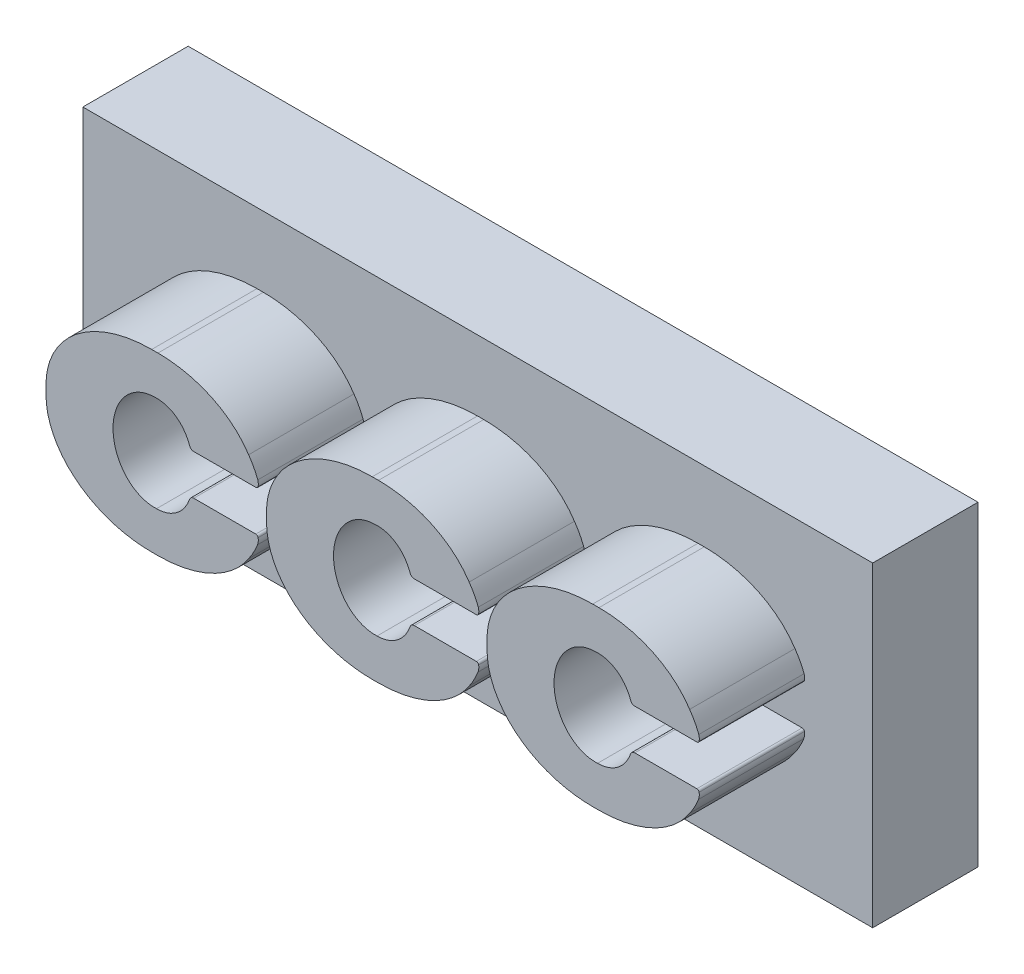
SolidWorks part; units mm, degrees
ref_plane "Front Plane" through (0, 0, 0) normal (0, 0, 1) x (1, 0, 0)
ref_plane "Top Plane" through (0, 0, 0) normal (0, 1, 0) x (1, 0, 0)
ref_plane "Right Plane" through (0, 0, 0) normal (1, 0, 0) x (0, 0, -1)
sketch "Sketch2" plane through (0, 0, 0) normal (0, 0, 1) x (1, 0, 0)
  line L0 (11.9717, 19.7341) -> (13.1563, 19.7341)
  line L1 (11.2915, 21.0135) -> (11.173, 21.0135)
  line L2 (9.1659, 19.4298) -> (9.1659, 19.265)
  line L3 (11.173, 17.6813) -> (11.2915, 17.6813)
  line L4 (13.1506, 18.9656) -> (11.9717, 18.9656)
  line L5 (7.784, 19.7341) -> (8.9686, 19.7341)
  line L6 (7.1038, 21.0135) -> (6.9853, 21.0135)
  line L7 (4.9781, 19.4298) -> (4.9781, 19.265)
  line L8 (6.9853, 17.6813) -> (7.1038, 17.6813)
  line L9 (8.9629, 18.9656) -> (7.784, 18.9656)
  line L10 (16.1595, 19.7341) -> (17.3441, 19.7341)
  line L11 (15.4793, 21.0135) -> (15.3608, 21.0135)
  line L12 (13.3536, 19.4298) -> (13.3536, 19.265)
  line L13 (15.3608, 17.6813) -> (15.4793, 17.6813)
  line L14 (17.3383, 18.9656) -> (16.1595, 18.9656)
  arc A0 (11.8937, 19.7892) -> (11.9717, 19.7341) centre (11.9717, 19.8169) ccw
  arc A1 (13.1563, 19.7341) -> (13.1934, 19.7655) centre (13.1507, 19.7782) ccw
  arc A2 (13.1934, 19.7655) -> (13.1881, 19.8762) centre (12.9648, 19.8101) ccw
  arc A3 (13.1881, 19.8762) -> (13.0144, 20.2019) centre (11.8185, 19.3553) ccw
  arc A4 (13.0144, 18.4929) -> (13.1821, 18.8047) centre (11.8303, 19.3304) ccw
  arc A5 (13.1821, 18.8047) -> (13.1945, 18.9287) centre (12.965, 18.8891) ccw
  arc A6 (13.1945, 18.9287) -> (13.1506, 18.9656) centre (13.1506, 18.9211) ccw
  arc A7 (11.9717, 18.9656) -> (11.8937, 18.9105) centre (11.9717, 18.8828) ccw
  arc A8 (7.7059, 19.7892) -> (7.784, 19.7341) centre (7.784, 19.8169) ccw
  arc A9 (8.9686, 19.7341) -> (9.0056, 19.7655) centre (8.963, 19.7782) ccw
  arc A10 (9.0056, 19.7655) -> (9.0003, 19.8762) centre (8.777, 19.8101) ccw
  arc A11 (9.0003, 19.8762) -> (8.8267, 20.2019) centre (7.6307, 19.3553) ccw
  arc A12 (8.8267, 18.4929) -> (8.9943, 18.8047) centre (7.6426, 19.3304) ccw
  arc A13 (8.9943, 18.8047) -> (9.0068, 18.9287) centre (8.7773, 18.8891) ccw
  arc A14 (9.0068, 18.9287) -> (8.9629, 18.9656) centre (8.9629, 18.9211) ccw
  arc A15 (7.784, 18.9656) -> (7.7059, 18.9105) centre (7.784, 18.8828) ccw
  arc A16 (16.0814, 19.7892) -> (16.1595, 19.7341) centre (16.1595, 19.8169) ccw
  arc A17 (17.3441, 19.7341) -> (17.3811, 19.7655) centre (17.3384, 19.7782) ccw
  arc A18 (17.3811, 19.7655) -> (17.3758, 19.8762) centre (17.1525, 19.8101) ccw
  arc A19 (17.3758, 19.8762) -> (17.2022, 20.2019) centre (16.0062, 19.3553) ccw
  arc A20 (17.2022, 18.4929) -> (17.3698, 18.8047) centre (16.0181, 19.3304) ccw
  arc A21 (17.3698, 18.8047) -> (17.3822, 18.9287) centre (17.1527, 18.8891) ccw
  arc A22 (17.3822, 18.9287) -> (17.3383, 18.9656) centre (17.3383, 18.9211) ccw
  arc A23 (16.1595, 18.9656) -> (16.0814, 18.9105) centre (16.1595, 18.8828) ccw
  ellipse E0 centre (11.225, 19.3476) end of major axis (11.2295, 18.4399) minor radius 0.7859 (11.1895, 20.2544) -> (11.2652, 18.441) ccw
  ellipse E1 centre (11.154, 19.3476) end of major axis (10.7962, 18.4848) minor radius 0.7645 (11.8937, 19.7892) -> (11.1895, 20.2544) ccw
  ellipse E2 centre (11.137, 19.3659) end of major axis (13.2165, 19.6762) minor radius 1.6361 (13.0144, 20.2019) -> (11.2915, 21.0135) ccw
  ellipse E3 centre (11.252, 19.3675) end of major axis (9.1698, 19.5312) minor radius 1.6429 (11.173, 21.0135) -> (9.1659, 19.4298) ccw
  ellipse E4 centre (11.252, 19.3273) end of major axis (13.3341, 19.4911) minor radius 1.6429 (9.1659, 19.265) -> (11.173, 17.6813) ccw
  ellipse E5 centre (11.137, 19.3289) end of major axis (9.0575, 19.6393) minor radius 1.6361 (11.2915, 17.6813) -> (13.0144, 18.4929) ccw
  ellipse E6 centre (11.154, 19.3521) end of major axis (11.5118, 18.4893) minor radius 0.7645 (11.2652, 18.441) -> (11.8937, 18.9105) ccw
  ellipse E7 centre (6.9663, 19.3476) end of major axis (6.6085, 18.4848) minor radius 0.7645 (7.7059, 19.7892) -> (7.0018, 20.2544) ccw
  ellipse E8 centre (6.9493, 19.3659) end of major axis (9.0288, 19.6762) minor radius 1.6361 (8.8267, 20.2019) -> (7.1038, 21.0135) ccw
  ellipse E9 centre (7.0643, 19.3675) end of major axis (4.9821, 19.5312) minor radius 1.6429 (6.9853, 21.0135) -> (4.9781, 19.4298) ccw
  ellipse E10 centre (7.0643, 19.3273) end of major axis (9.1464, 19.4911) minor radius 1.6429 (4.9781, 19.265) -> (6.9853, 17.6813) ccw
  ellipse E11 centre (6.9493, 19.3289) end of major axis (9.0288, 19.0186) minor radius 1.6361 (7.1038, 17.6813) -> (8.8267, 18.4929) ccw
  ellipse E12 centre (6.9663, 19.3521) end of major axis (7.3241, 18.4893) minor radius 0.7645 (7.0775, 18.441) -> (7.7059, 18.9105) ccw
  ellipse E13 centre (7.0373, 19.3476) end of major axis (7.0418, 18.4399) minor radius 0.7859 (7.0018, 20.2544) -> (7.0775, 18.441) ccw
  ellipse E14 centre (15.4127, 19.3476) end of major axis (15.4173, 18.4399) minor radius 0.7859 (15.3772, 20.2544) -> (15.4529, 18.441) ccw
  ellipse E15 centre (15.3417, 19.3476) end of major axis (14.984, 18.4848) minor radius 0.7645 (16.0814, 19.7892) -> (15.3772, 20.2544) ccw
  ellipse E16 centre (15.3248, 19.3659) end of major axis (17.4043, 19.6762) minor radius 1.6361 (17.2022, 20.2019) -> (15.4793, 21.0135) ccw
  ellipse E17 centre (15.4397, 19.3675) end of major axis (13.3576, 19.5312) minor radius 1.6429 (15.3608, 21.0135) -> (13.3536, 19.4298) ccw
  ellipse E18 centre (15.4397, 19.3273) end of major axis (17.5219, 19.4911) minor radius 1.6429 (13.3536, 19.265) -> (15.3608, 17.6813) ccw
  ellipse E19 centre (15.3248, 19.3289) end of major axis (13.2452, 19.6393) minor radius 1.6361 (15.4793, 17.6813) -> (17.2022, 18.4929) ccw
  ellipse E20 centre (15.3417, 19.3521) end of major axis (15.6995, 18.4893) minor radius 0.7645 (15.4529, 18.441) -> (16.0814, 18.9105) ccw
extrude "Boss-Extrude1" add sketch "Sketch2" along normal blind 2
sketch "Sketch3" plane through (0, 0, 0) normal (0, 0, -1) x (-1, 0, 0)
  line L1 (-18.6781, 22.3475) -> (-3.6781, 22.3475)
  line L2 (-18.6781, 22.3475) -> (-18.6781, 16.3475)
  line L3 (-18.6781, 16.3475) -> (-3.6781, 16.3475)
  line L4 (-3.6781, 22.3475) -> (-3.6781, 16.3475)
  dimension "D1" = 15
  dimension "D2" = 6
  dimension "D3" = 1.3
  dimension "D4" = 1.334
extrude "Boss-Extrude2" add sketch "Sketch3" along normal blind 2
